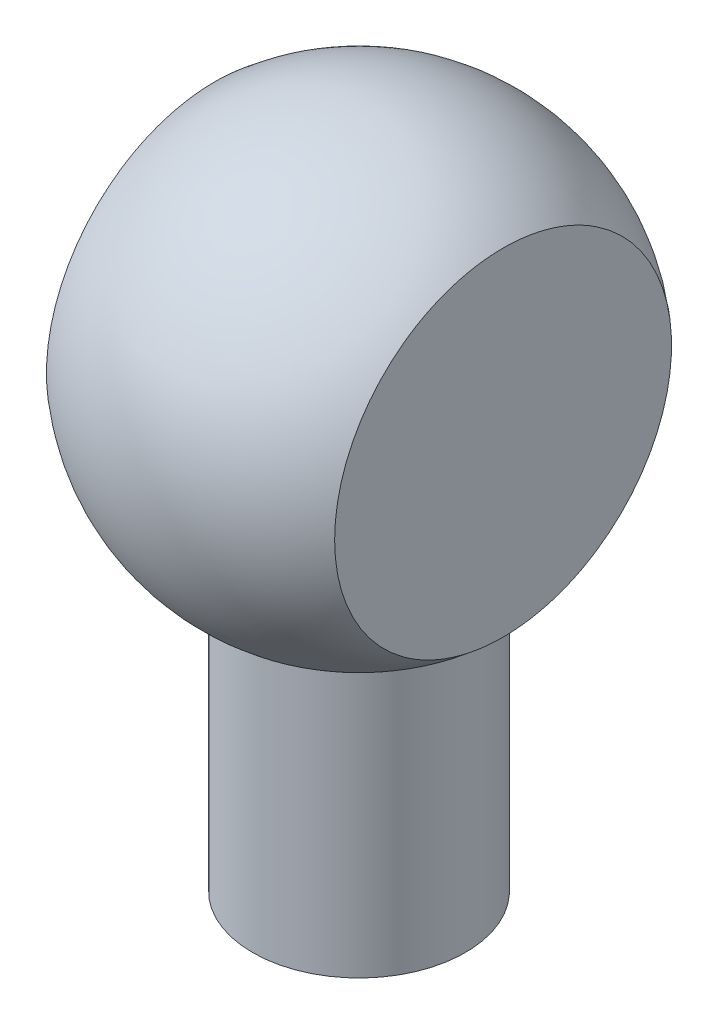
SolidWorks part; units mm, degrees
ref_plane "Alzado" through (0, 0, 0) normal (0, 0, 1) x (1, 0, 0)
ref_plane "Planta" through (0, 0, 0) normal (0, 1, 0) x (1, 0, 0)
ref_plane "Vista lateral" through (0, 0, 0) normal (1, 0, 0) x (0, 0, -1)
sketch "Croquis1" plane through (0, 0, 0) normal (1, 0, 0) x (0, 0, -1)
  line L0 (0, 0) -> (-4.8, 0)
  line L1 (-4.8, 0) -> (-4.8, 12)
  line L2 (0, 20.7727) -> (0, 0) construction
  line L3 (0, 0) -> (0, 30.7727)
  arc A0 (-4.8, 12) -> (0, 30.7727) centre (0, 20.7727) cw
  dimension "D2" = 12
  dimension "D3" = 10
  dimension "D1" = 4.8
  dimension "D4" = 18.7727
revolve "Revolución1" add sketch "Croquis1" angle 360 about L2
ref_plane "Plano1" through (0, 35, 0) normal (0, 1, 0) x (1, 0, 0)
sketch "Croquis2" plane through (0, 35, 0) normal (0, 1, 0) x (1, 0, 0)
  line L0 (0, 0) -> (0, 11.6596) construction
  line L1 (-12.9945, 11.6596) -> (-6.5, 11.6596)
  line L2 (-12.9945, 11.6596) -> (-12.9945, -11.2584)
  line L3 (-12.9945, -11.2584) -> (-6.5, -11.2584)
  line L4 (-6.5, 11.6596) -> (-6.5, -11.2584)
  line L5 (12.9945, -11.2584) -> (6.5, -11.2584)
  line L6 (6.5, 11.6596) -> (6.5, -11.2584)
  line L7 (12.9945, 11.6596) -> (6.5, 11.6596)
  line L8 (12.9945, 11.6596) -> (12.9945, -11.2584)
  dimension "D1" = 6.5
extrude "Cortar-Extruir1" cut sketch "Croquis2" against normal blind 23
